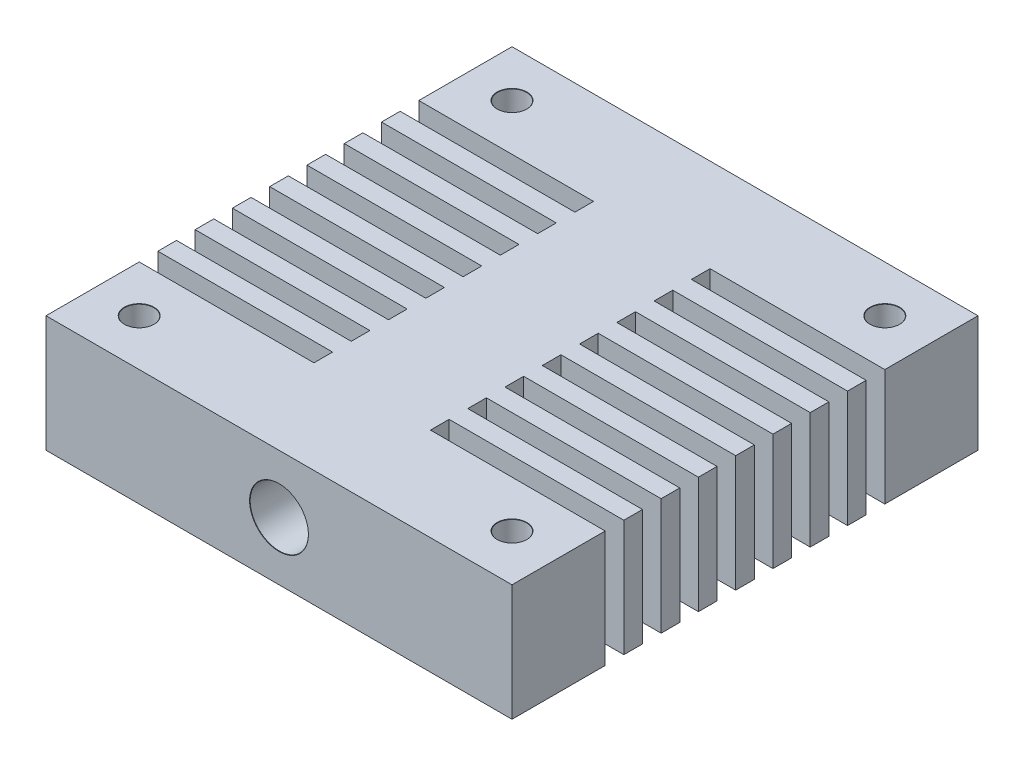
SolidWorks part; units mm, degrees
ref_plane "Plan de face" through (0, 0, 0) normal (0, 0, 1) x (1, 0, 0)
ref_plane "Plan de dessus" through (0, 0, 0) normal (0, 1, 0) x (1, 0, 0)
ref_plane "Plan de droite" through (0, 0, 0) normal (1, 0, 0) x (0, 0, -1)
sketch "Esquisse1" plane through (0, 0, 0) normal (0, 1, 0) x (1, 0, 0)
  line L1 (0, 0) -> (40, 0)
  line L2 (0, 0) -> (0, 40)
  line L3 (0, 40) -> (40, 40)
  line L4 (40, 0) -> (40, 40)
  dimension "D1" = 40
  dimension "D2" = 40
extrude "Boss.-Extru.1" add sketch "Esquisse1" along normal blind 10
sketch "Esquisse4" plane through (0, 0, 0) normal (0, 0, 1) x (1, 0, 0)
  line L0 (0, 10) -> (40, 10) construction
  line L1 (40, 10) -> (40, 0) construction
  circle A0 centre (20, 5) radius 2
  dimension "D1" = 4
  dimension "D2" = 5
  dimension "D3" = 20
hole_wizard "Diamètre du perçage Ø4.0 (4)1" positions "Esquisse6" profile "Esquisse5" hole size "Ø4.0" standard "ISO" end condition through all
sketch "Esquisse6" plane through (0, 0, 0) normal (0, 0, 1) x (1, 0, 0)
  point P0 (20, 5)
sketch "Esquisse5" plane through (20, 5, 0) normal (1, 0, 0) x (0, -1, 0)
  line L0 (0, 0) -> (0, 40)
  line L1 (0, 40) -> (2, 40)
  line L2 (2, 40) -> (2, 0)
  line L5 (2, 0) -> (0, 0)
  line L11 (0, -6.35) -> (0, 107.95) construction
  dimension "Diamètre du perçage jusqu'au prochain" = 4
  dimension "Profondeur du perçage jusqu'au prochain" = 40
sketch "Esquisse2" plane through (0, 0, 0) normal (0, 0, 1) x (1, 0, 0)
  line L0 (40, 10) -> (40, 0) construction
  line L1 (0, 10) -> (40, 10) construction
  circle A0 centre (20, 5) radius 3
  dimension "D1" = 6
  dimension "D2" = 20
  dimension "D3" = 5
hole_wizard "Trou pour taraudage pour trou taraudé M61" positions "Esquisse8" profile "Esquisse9" hole size "M6" standard "ISO"
sketch "Esquisse8" plane through (0, 0, 0) normal (0, 0, 1) x (1, 0, 0)
  point P0 (20, 5)
sketch "Esquisse9" plane through (20, 5, 0) normal (1, 0, 0) x (0, -1, 0)
  line L0 (0, 0) -> (0, 9.5022)
  line L1 (0, 9.5022) -> (2.5, 8)
  line L2 (2.5, 8) -> (2.5, 0.025)
  line L3 (2.5, 0.025) -> (2.525, 0)
  line L5 (2.525, 0) -> (0, 0)
  line L6 (-2.5, 0.025) -> (-2.525, 0) construction
  line L10 (0, 9.5022) -> (-2.5, 8) construction
  line L11 (0, -6.35) -> (0, 107.95) construction
  dimension "Diamètre du perçage" = 5
  dimension "Profondeur du perçage" = 8
  dimension "Diamètre du fraisage entrant" = 5.05
  dimension "Angle du fraisage entrant" = 90
  dimension "Angle de pointe" = 118
sketch "Esquisse3" plane through (0, 0, -40) normal (0, 0, -1) x (-1, 0, 0)
  line L0 (-40, 10) -> (-40, 0) construction
  line L1 (-40, 10) -> (0, 10) construction
  circle A0 centre (-20, 5) radius 3
  dimension "D1" = 6
  dimension "D2" = 20
  dimension "D3" = 5
hole_wizard "Diamètre du perçage Ø6.0 (6)1" positions "Esquisse11" profile "Esquisse12" hole size "Ø6.0" standard "ISO"
sketch "Esquisse11" plane through (0, 0, -40) normal (0, 0, -1) x (-1, 0, 0)
  point P0 (-20, 5)
sketch "Esquisse12" plane through (20, 5, -40) normal (1, 0, 0) x (0, 1, 0)
  line L0 (0, 0) -> (0, 21.8026)
  line L1 (0, 21.8026) -> (3, 20)
  line L2 (3, 20) -> (3, 0)
  line L5 (3, 0) -> (0, 0)
  line L10 (0, 21.8026) -> (-3, 20) construction
  line L11 (0, -6.35) -> (0, 107.95) construction
  dimension "Diamètre du perçage" = 6
  dimension "Profondeur du perçage" = 20
  dimension "Angle de pointe" = 118
sketch "Esquisse16" plane through (0, 0, 0) normal (0, -1, 0) x (1, 0, 0)
  line L0 (0, 0) -> (40, 0) construction
  line L1 (0, -40) -> (0, 0) construction
  line L2 (40, 0) -> (40, -40) construction
  line L3 (40, -40) -> (0, -40) construction
  circle A0 centre (4, -4) radius 1.5
  circle A1 centre (36, -4) radius 1.5
  circle A2 centre (36, -36) radius 1.5
  circle A3 centre (4, -36) radius 1.5
  circle A4 centre (20, -36) radius 1.5
  dimension "D3" = 3
  dimension "D6" = 3
  dimension "D7" = 3
  dimension "D10" = 3
  dimension "D11" = 20
  dimension "D15" = 3
  dimension "D1" = 4
  dimension "D2" = 4
  dimension "D4" = 4
  dimension "D5" = 4
  dimension "D8" = 4
  dimension "D9" = 4
  dimension "D12" = 4
  dimension "D13" = 4
  dimension "D14" = 4
hole_wizard "Trou pour taraudage pour trou taraudé M31" positions "Esquisse18" profile "Esquisse17" hole size "M3" standard "ISO" end condition through all
sketch "Esquisse18" plane through (0, 0, 0) normal (0, -1, 0) x (-1, 0, 0)
  point P0 (-4, 4)
  point P3 (-36, 4)
  point P6 (-36, 36)
  point P9 (-4, 36)
sketch "Esquisse17" plane through (4, 0, -4) normal (1, 0, 0) x (0, 0, -1)
  line L0 (0, 0) -> (0, 10)
  line L1 (0, 10) -> (1.275, 10)
  line L2 (1.25, 9.975) -> (1.25, 0.025)
  line L3 (1.25, 0.025) -> (1.275, 0)
  line L5 (1.275, 0) -> (0, 0)
  line L6 (-1.25, 0.025) -> (-1.275, 0) construction
  line L7 (1.275, 10) -> (1.25, 9.975)
  line L8 (-1.275, 10) -> (-1.25, 9.975) construction
  line L11 (0, -6.35) -> (0, 107.95) construction
  dimension "Diamètre du perçage jusqu'au prochain" = 2.5
  dimension "Profondeur du perçage jusqu'au prochain" = 10
  dimension "Diamètre du fraisage entrant" = 2.55
  dimension "Angle du fraisage entrant" = 90
  dimension "Diamètre du fraisage débouchant" = 2.55
  dimension "Angle du fraisage débouchant" = 90
hole_wizard "Trou pour taraudage pour trou taraudé M32" positions "Esquisse20" profile "Esquisse19" hole size "M3" standard "ISO"
sketch "Esquisse20" plane through (0, 0, 0) normal (0, -1, 0) x (-1, 0, 0)
  point P0 (-20, 36)
sketch "Esquisse19" plane through (20, 0, -36) normal (1, 0, 0) x (0, 0, -1)
  line L0 (0, 0) -> (0, 5.7511)
  line L1 (0, 5.7511) -> (1.25, 5)
  line L2 (1.25, 5) -> (1.25, 0.025)
  line L3 (1.25, 0.025) -> (1.275, 0)
  line L5 (1.275, 0) -> (0, 0)
  line L6 (-1.25, 0.025) -> (-1.275, 0) construction
  line L10 (0, 5.7511) -> (-1.25, 5) construction
  line L11 (0, -6.35) -> (0, 107.95) construction
  dimension "Diamètre du perçage" = 2.5
  dimension "Profondeur du perçage" = 5
  dimension "Diamètre du fraisage entrant" = 2.55
  dimension "Angle du fraisage entrant" = 90
  dimension "Angle de pointe" = 118
sketch "Esquisse21" plane through (0, 0, 0) normal (0, -1, 0) x (1, 0, 0)
  line L0 (0, -40) -> (0, 0) construction
  line L1 (0, -8) -> (15, -8)
  line L2 (0, -8) -> (0, -9.6)
  line L3 (0, -9.6) -> (15, -9.6)
  line L4 (15, -8) -> (15, -9.6)
  line L5 (0, 0) -> (40, 0) construction
  line L6 (40, 0) -> (40, -40) construction
  line L7 (40, -8) -> (25, -8)
  line L8 (40, -8) -> (40, -9.6)
  line L9 (40, -9.6) -> (25, -9.6)
  line L10 (25, -8) -> (25, -9.6)
  dimension "D1" = 1.6
  dimension "D2" = 15
  dimension "D3" = 8
  dimension "D4" = 1.6
  dimension "D5" = 8
  dimension "D6" = 15
extrude "Enlèv. mat.-Extru.1" cut sketch "Esquisse21" against normal through all
pattern_linear "Répétition linéaire1" count 8 spacing 3.2 along (0, 0, -1) of "Enlèv. mat.-Extru.1"
